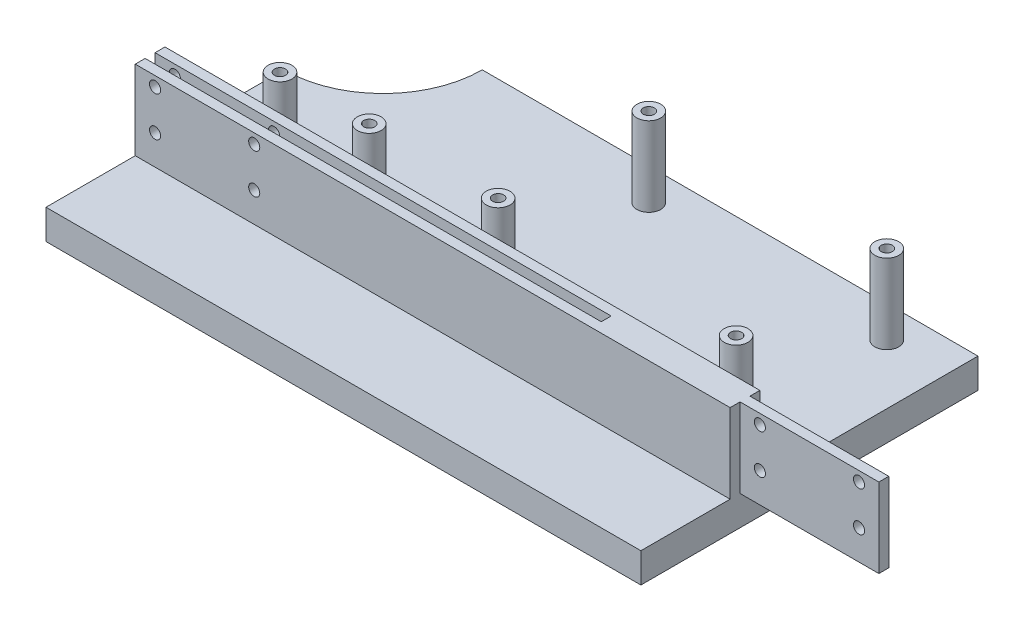
SolidWorks part; units mm, degrees
ref_plane "Front Plane" through (0, 0, 0) normal (0, 0, 1) x (1, 0, 0)
ref_plane "Top Plane" through (0, 0, 0) normal (0, 1, 0) x (1, 0, 0)
ref_plane "Right Plane" through (0, 0, 0) normal (1, 0, 0) x (0, 0, -1)
sketch "Sketch1" plane through (0, 0, 0) normal (0, 1, 0) x (1, 0, 0)
  line L1 (25, 85) -> (150, 85)
  line L2 (0, 60) -> (0, 0)
  line L3 (0, 0) -> (150, 0)
  line L4 (150, 85) -> (150, 0)
  arc A0 (0, 60) -> (25, 85) centre (0, 85) ccw
  dimension "D2" = 50
  dimension "D1" = 150
  dimension "D3" = 60
extrude "Boss-Extrude1" add sketch "Sketch1" along normal blind 7.5
sketch "Sketch2" plane through (0, 7.5, 0) normal (0, 1, 0) x (1, 0, 0)
  line L0 (0, 60) -> (0, 0) construction
  line L1 (0, 30) -> (150, 30)
  line L2 (0, 30) -> (0, 27.5)
  line L3 (0, 27.5) -> (150, 27.5)
  line L4 (150, 30) -> (150, 27.5)
  line L5 (150, 0) -> (150, 85) construction
  line L7 (0, 25) -> (150, 25)
  line L8 (0, 25) -> (0, 22.5)
  line L9 (0, 22.5) -> (150, 22.5)
  line L10 (150, 25) -> (150, 22.5)
  line L11 (115, 27.5) -> (185, 27.5)
  line L12 (115, 27.5) -> (115, 25)
  line L13 (115, 25) -> (185, 25)
  line L14 (185, 27.5) -> (185, 25)
  line L15 (0, 0) -> (150, 0) construction
  point P16 (150, 27.5)
  line M13 (150, 0) -> (150, 85)
  line M16 (0, 60) -> (0, 0)
  dimension "D1" = 2.5
  dimension "D2" = 70
  dimension "D3" = 25
extrude "Boss-Extrude2" add sketch "Sketch2" along normal blind 20 contours L14 L11 L13 M13 | L3 L12 L7 M13 | L9 L7 M16 M13
sketch "Sketch3" plane through (0, 0, -22.5) normal (0, 0, 1) x (1, 0, 0)
  line L0 (30, 25) -> (30, 15) construction
  line L1 (30, 15) -> (5, 15) construction
  line L2 (5, 15) -> (5, 25) construction
  line L3 (5, 25) -> (30, 25) construction
  line L4 (0, 27.5) -> (150, 27.5) construction
  line L5 (0, 27.5) -> (0, 7.5) construction
  circle A0 centre (5, 25) radius 1.4
  circle A1 centre (5, 15) radius 1.4
  circle A2 centre (30, 25) radius 1.4
  circle A3 centre (30, 15) radius 1.4
  dimension "D1" = 2.8
  dimension "D2" = 25
  dimension "D3" = 10
  dimension "D4" = 2.5
  dimension "D5" = 5
extrude "Cut-Extrude1" cut sketch "Sketch3" against normal blind 10
sketch "Sketch4" plane through (0, 0, -25) normal (0, 0, 1) x (1, 0, 0)
  line L0 (150, 27.5) -> (185, 27.5) construction
  line L1 (185, 27.5) -> (185, 7.5) construction
  line L2 (155, 25) -> (155, 15) construction
  line L3 (155, 15) -> (180, 15) construction
  line L4 (180, 15) -> (180, 25) construction
  line L5 (180, 25) -> (155, 25) construction
  circle A0 centre (155, 25) radius 1.4
  circle A1 centre (180, 25) radius 1.4
  circle A2 centre (180, 15) radius 1.4
  circle A3 centre (155, 15) radius 1.4
  dimension "D1" = 2.8
  dimension "D2" = 2.5
  dimension "D3" = 5
  dimension "D4" = 25
  dimension "D5" = 10
extrude "Cut-Extrude2" cut sketch "Sketch4" against normal blind 10
sketch "Sketch5" plane through (0, 7.5, 0) normal (0, 1, 0) x (1, 0, 0)
  line L0 (20, 39) -> (42.5, 39) construction
  line L1 (42.5, 39) -> (42.5, 0) construction
  line L2 (0, 0) -> (150, 0) construction
  line L3 (0, 60) -> (0, 30) construction
  line L4 (75, 77) -> (135, 77) construction
  line L5 (135, 77) -> (135, 39) construction
  line L6 (135, 39) -> (75, 39) construction
  line L7 (75, 39) -> (75, 77) construction
  line L8 (150, 30) -> (150, 85) construction
  circle A0 centre (20, 39) radius 3
  circle A1 centre (42.5, 39) radius 3
  circle A2 centre (75, 77) radius 3
  circle A3 centre (135, 77) radius 3
  circle A4 centre (135, 39) radius 3
  circle A5 centre (75, 39) radius 3
  dimension "D4" = 6
  dimension "D9" = 6
  dimension "D1" = 22.5
  dimension "D2" = 39
  dimension "D3" = 20
  dimension "D5" = 38
  dimension "D6" = 60
  dimension "D7" = 15
  dimension "D8" = 39
extrude "Boss-Extrude3" add sketch "Sketch5" along normal blind 20
sketch "Sketch6" plane through (0, 27.5, 0) normal (0, 1, 0) x (1, 0, 0)
  circle A0 centre (20, 39) radius 1.4
  circle A1 centre (42.5, 39) radius 1.4
  circle A2 centre (75, 77) radius 1.4
  circle A3 centre (75, 39) radius 1.4
  circle A4 centre (135, 39) radius 1.4
  circle A5 centre (135, 77) radius 1.4
  dimension "D1" = 2.8
extrude "Cut-Extrude3" cut sketch "Sketch6" against normal blind 8
